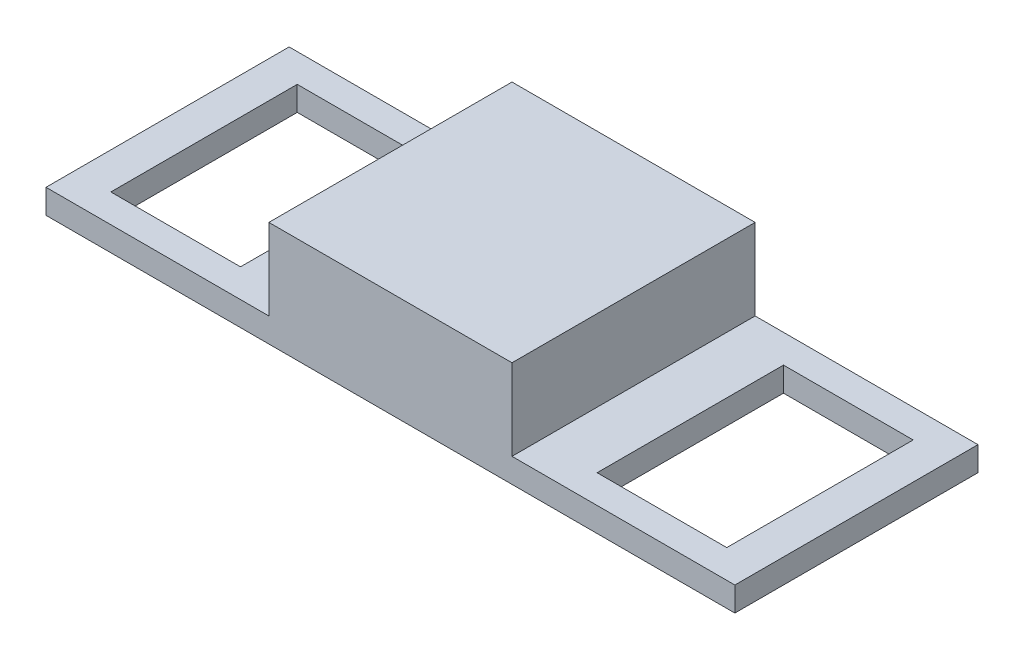
SolidWorks part; units mm, degrees
ref_plane "Front Plane" through (0, 0, 0) normal (0, 0, 1) x (1, 0, 0)
ref_plane "Top Plane" through (0, 0, 0) normal (0, 1, 0) x (1, 0, 0)
ref_plane "Right Plane" through (0, 0, 0) normal (1, 0, 0) x (0, 0, -1)
sketch "Croquis1" plane through (0, 0, 0) normal (0, 1, 0) x (1, 0, 0)
  line L1 (-42.5, -15) -> (42.5, -15)
  line L2 (-42.5, -15) -> (-42.5, 15)
  line L3 (-42.5, 15) -> (42.5, 15)
  line L4 (42.5, -15) -> (42.5, 15)
  line L5 (-42.5, -15) -> (42.5, 15) construction
  line L6 (-42.5, 15) -> (42.5, -15) construction
  line L11 (22, -11.5) -> (22, 11.5)
  line L12 (-38, -11.5) -> (-22, -11.5)
  line L13 (0, 0) -> (0, 50000) construction
  line L18 (-38, -11.5) -> (-38, 11.5)
  line L19 (-38, 11.5) -> (-22, 11.5)
  line L20 (-22, -11.5) -> (-22, 11.5)
  line L21 (-38, -11.5) -> (-22, 11.5) construction
  line L22 (-38, 11.5) -> (-22, -11.5) construction
  line L23 (38, -11.5) -> (22, -11.5)
  line L24 (38, -11.5) -> (38, 11.5)
  line L25 (38, 11.5) -> (22, 11.5)
  point P0 (0, 0)
  point P5 (-30, 0)
  dimension "D1" = 85
  dimension "D2" = 16
  dimension "D3" = 23
  dimension "D4" = 30
extrude "Saliente-Extruir1" add sketch "Croquis1" along normal blind 3
sketch "Croquis3" plane through (0, 3, 0) normal (0, 1, 0) x (1, 0, 0)
  line L0 (42.5, 15) -> (-42.5, 15) construction
  line L1 (-15, -15) -> (15, -15)
  line L2 (-15, -15) -> (-15, 15)
  line L3 (-15, 15) -> (15, 15)
  line L4 (15, -15) -> (15, 15)
  line L5 (-15, -15) -> (15, 15) construction
  line L6 (-15, 15) -> (15, -15) construction
  point P0 (0, 0)
  dimension "D1" = 30
extrude "Saliente-Extruir2" add sketch "Croquis3" along normal blind 10
